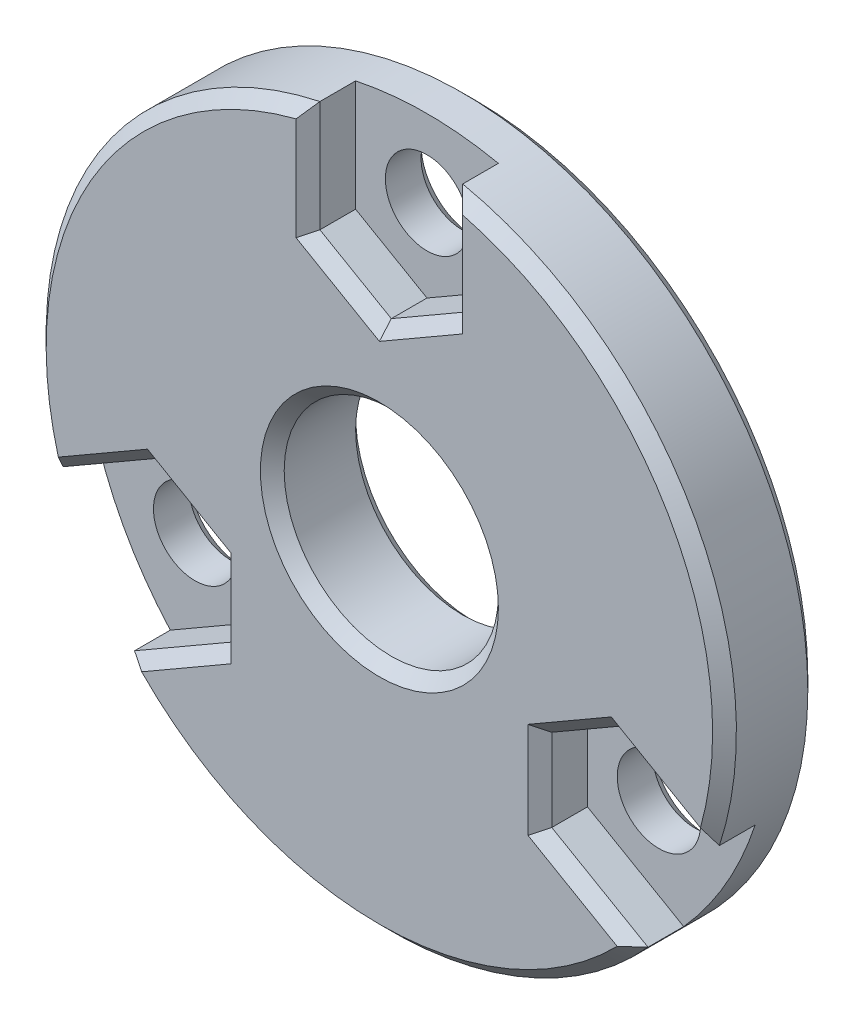
SolidWorks part; units mm, degrees
ref_plane "Front Plane" through (0, 0, 0) normal (0, 0, 1) x (1, 0, 0)
ref_plane "Top Plane" through (0, 0, 0) normal (0, 1, 0) x (1, 0, 0)
ref_plane "Right Plane" through (0, 0, 0) normal (1, 0, 0) x (0, 0, -1)
sketch "Sketch4" plane through (0, 0, 0) normal (0, 0, 1) x (1, 0, 0)
  circle A0 centre (0, 0) radius 9.5 construction
  circle A1 centre (0, 11.25) radius 1.75
  circle A2 centre (9.7428, -5.625) radius 1.75
  circle A3 centre (-9.7428, -5.625) radius 1.75
  circle A4 centre (0, 0) radius 14.5
  circle A5 centre (0, 0) radius 4.5
  point P11 (0, 0)
  dimension "D1" = 19
  dimension "D2" = 3.5
  dimension "D4" = 5
  dimension "D5" = 5
  dimension "D3" = 3
extrude "Boss-Extrude5" add sketch "Sketch4" along normal blind 4
sketch "Sketch5" plane through (0, 0, 4) normal (0, 0, 1) x (1, 0, 0)
  line L0 (12.7428, -3.8929) -> (9.7428, -2.1609)
  line L1 (0, 14.7141) -> (-3, 12.9821) construction
  line L2 (-3, 12.9821) -> (-3, 9.5179)
  line L3 (-3, 9.5179) -> (0, 7.7859)
  line L4 (0, 7.7859) -> (3, 9.5179)
  line L5 (3, 9.5179) -> (3, 12.9821)
  line L6 (3, 12.9821) -> (0, 14.7141) construction
  line L7 (9.7428, -2.1609) -> (6.7428, -3.8929)
  line L8 (6.7428, -3.8929) -> (6.7428, -7.3571)
  line L9 (6.7428, -7.3571) -> (9.7428, -9.0891)
  line L10 (12.7428, -3.8929) -> (14.4748, -4.8929)
  line L11 (14.4748, -4.8929) -> (11.4748, -10.0891)
  line L12 (11.4748, -10.0891) -> (9.7428, -9.0891)
  line L13 (12.7428, -7.3571) -> (12.7428, -3.8929) construction
  line L14 (9.7428, -9.0891) -> (12.7428, -7.3571) construction
  line L15 (-9.7428, -9.0891) -> (-6.7428, -7.3571)
  line L16 (-6.7428, -7.3571) -> (-6.7428, -3.8929)
  line L17 (-6.7428, -3.8929) -> (-9.7428, -2.1609)
  line L18 (-3, 12.9821) -> (-3, 14.9821)
  line L19 (-3, 14.9821) -> (3, 14.9821)
  line L20 (3, 14.9821) -> (3, 12.9821)
  line L21 (-9.7428, -2.1609) -> (-12.7428, -3.8929)
  line L22 (-9.7428, -9.0891) -> (-11.4748, -10.0891)
  line L23 (-11.4748, -10.0891) -> (-14.4748, -4.8929)
  line L24 (-14.4748, -4.8929) -> (-12.7428, -3.8929)
  line L25 (-12.7428, -7.3571) -> (-9.7428, -9.0891) construction
  line L26 (-12.7428, -3.8929) -> (-12.7428, -7.3571) construction
  circle A0 centre (0, 11.25) radius 3 construction
  circle A1 centre (9.7428, -5.625) radius 3 construction
  circle A2 centre (-9.7428, -5.625) radius 3 construction
  point P36 (0, 0)
  dimension "D1" = 6
  dimension "D3" = 2
  dimension "D2" = 3
extrude "Cut-Extrude1" cut sketch "Sketch5" against normal blind 2
chamfer "Chamfer1" distance 0.5 angle 45 21 edges at (-12.5574, 7.25, 4) (-3, 11.8521, 4) (-1.5, 8.6519, 4) (1.5, 8.6519, 4) (3, 11.8521, 4) (12.5574, 7.25, 4) (11.7642, -3.328, 4) (8.2428, -3.0269, 4) (6.7428, -5.625, 4) (8.7642, -8.5241, 4) (0, -14.5, 4) (-8.7642, -8.5241, 4) (-6.7428, -5.625, 4) (-8.2428, -3.0269, 4) (-11.7642, -3.328, 4) (4.5, 0, 0) (4.5, 0, 4) (-7.9928, -5.625, 0) (1.75, 11.25, 0) (11.4928, -5.625, 0) (14.5, 0, 0)
